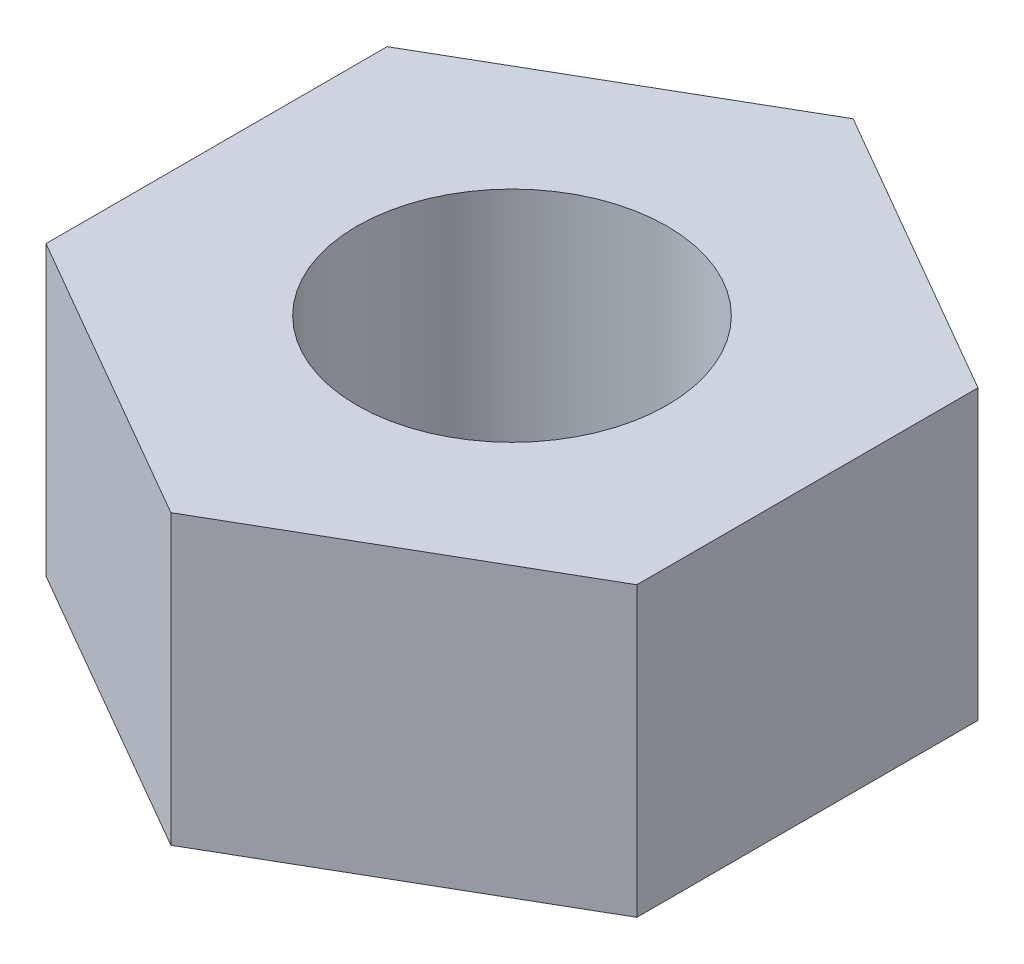
SolidWorks part; units mm, degrees
ref_plane "前视基准面" through (0, 0, 0) normal (0, 0, 1) x (1, 0, 0)
ref_plane "上视基准面" through (0, 0, 0) normal (0, 1, 0) x (1, 0, 0)
ref_plane "右视基准面" through (0, 0, 0) normal (1, 0, 0) x (0, 0, -1)
sketch "草图1" plane through (0, 0, 0) normal (0, 1, 0) x (1, 0, 0)
  line L1 (4, -2.3094) -> (4, 2.3094)
  line L2 (4, 2.3094) -> (0, 4.6188)
  line L3 (0, 4.6188) -> (-4, 2.3094)
  line L4 (-4, 2.3094) -> (-4, -2.3094)
  line L5 (-4, -2.3094) -> (0, -4.6188)
  line L6 (0, -4.6188) -> (4, -2.3094)
  circle A0 centre (0, 0) radius 4 construction
  dimension "D1" = 8
extrude "凸台-拉伸1" add sketch "草图1" along normal blind 3.9
sketch "草图4" plane through (0, 0, 0) normal (0, -1, 0) x (1, 0, 0)
  point P0 (0, 0)
hole_wizard "M5 螺纹孔1" positions "3D草图2" profile "草图5" tap size "M5" standard "GB" end condition through all
sketch3d "3D草图2"
  point P0 (0, 0, 0)
  point P3 (0, 0, 0)
sketch "草图5" plane through (0, 0, 0) normal (1, 0, 0) x (0, 0, -1)
  line L0 (0, 0) -> (0, 3.9)
  line L1 (0, 3.9) -> (2.1, 3.9)
  line L2 (2.1, 3.9) -> (2.1, 0)
  line L5 (2.1, 0) -> (0, 0)
  line L11 (0, -6.35) -> (0, 107.95) construction
  dimension "通孔螺纹孔钻头直径" = 4.2
  dimension "通孔螺纹孔钻头深度" = 3.9
cosmetic thread "孔螺蚊线1" parameters "D2"=5
cosmetic thread "孔螺蚊线2" parameters "D2"=5
